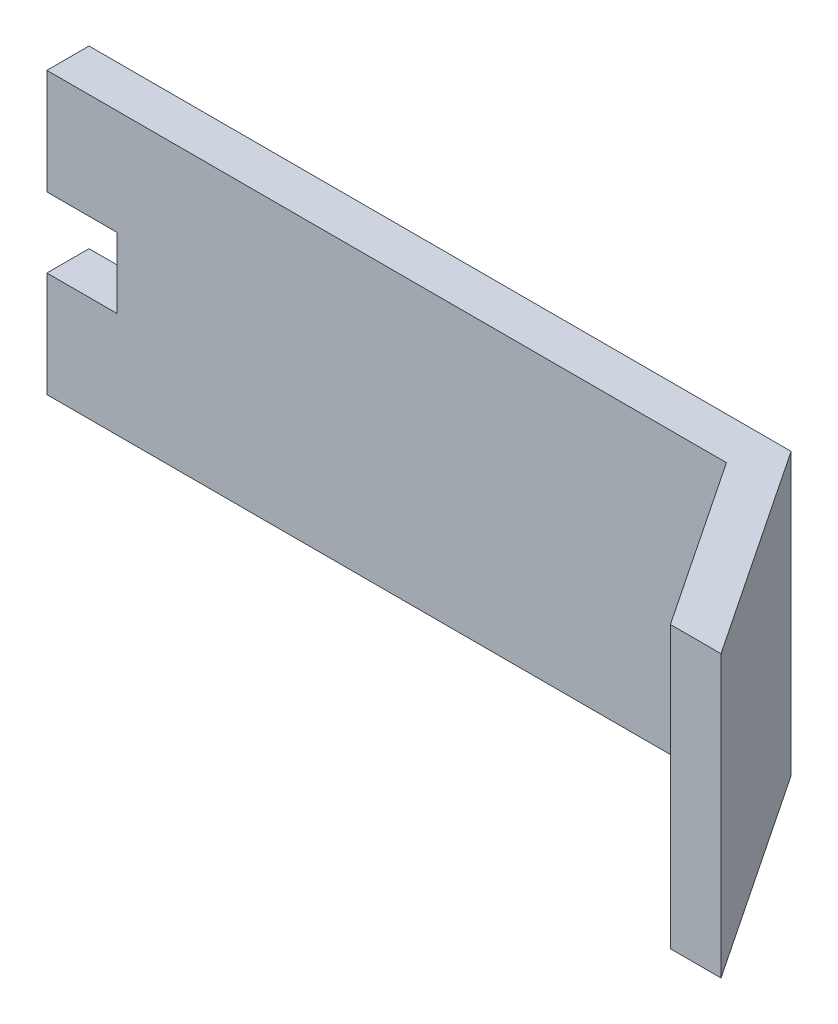
SolidWorks part; units mm, degrees
ref_plane "Front Plane" through (0, 0, 0) normal (0, 0, 1) x (1, 0, 0)
ref_plane "Top Plane" through (0, 0, 0) normal (0, 1, 0) x (1, 0, 0)
ref_plane "Right Plane" through (0, 0, 0) normal (1, 0, 0) x (0, 0, -1)
sketch "Sketch1" plane through (0, 0, 0) normal (0, 1, 0) x (1, 0, 0)
  line L0 (0, 0) -> (0, 3)
  line L1 (0, 3) -> (50, 3)
  line L2 (50, 3) -> (59.9846, -11.9769)
  line L3 (0, 0) -> (48.3944, 0)
  line L4 (48.3944, 0) -> (56.379, -11.9769)
  line L5 (56.379, -11.9769) -> (59.9846, -11.9769)
  dimension "D1" = 3
  dimension "D2" = 3
  dimension "D3" = 56.31
  dimension "D4" = 18
  dimension "D5" = 50
extrude "Boss-Extrude1" add sketch "Sketch1" along normal blind 20
sketch "Sketch2" plane through (0, 0, -3) normal (0, 0, -1) x (-1, 0, 0)
  line L0 (0, 12.5) -> (-5, 12.5)
  line L1 (0, 20) -> (0, 0) construction
  line L2 (-5, 12.5) -> (-5, 7.5)
  line L3 (-5, 7.5) -> (0, 7.5)
  line L4 (0, 12.5) -> (0, 20) construction
  line L5 (0, 7.5) -> (0, 0) construction
  line L6 (0, 12.5) -> (0, 7.5)
  dimension "D1" = 5
  dimension "D2" = 5
extrude "Cut-Extrude1" cut sketch "Sketch2" against normal blind 10
